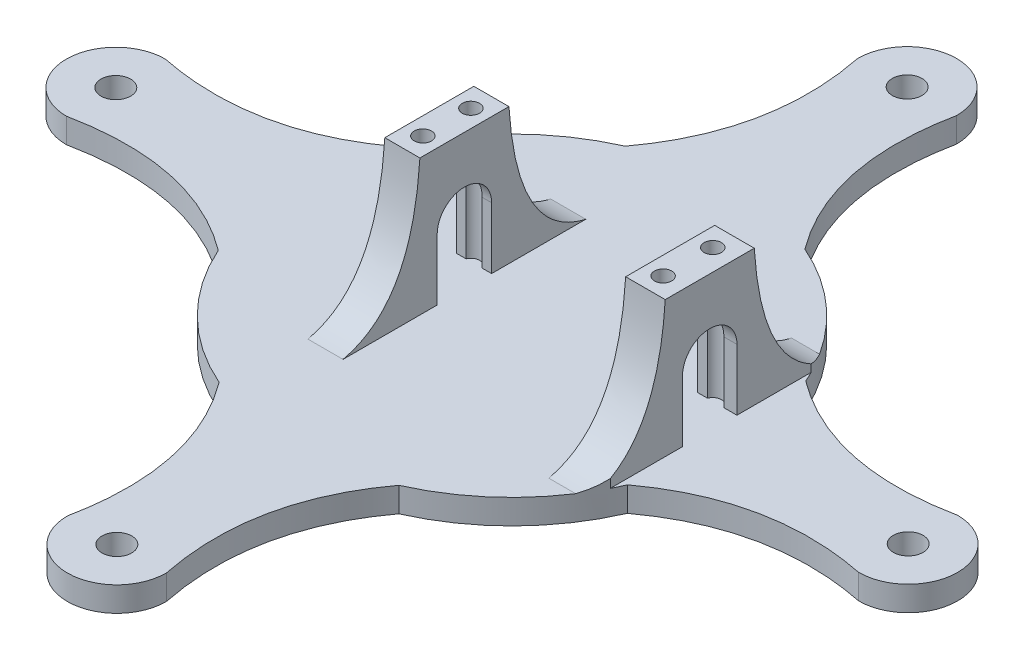
SolidWorks part; units mm, degrees
ref_plane "Vorne" through (0, 0, 0) normal (0, 0, 1) x (1, 0, 0)
ref_plane "Oben" through (0, 0, 0) normal (0, 1, 0) x (1, 0, 0)
ref_plane "Rechts" through (0, 0, 0) normal (1, 0, 0) x (0, 0, -1)
sketch "Skizze1" plane through (0, 0, 0) normal (0, 1, 0) x (1, 0, 0)
  circle A0 centre (0, 0) radius 45
  dimension "D1" = 90
extrude "Aufsatz-Linear austragen1" add sketch "Skizze1" along normal blind 5
sketch "Skizze3" plane through (0, 5, 0) normal (0, 1, 0) x (1, 0, 0)
  line L1 (-16.5343, 8.8163) -> (-8.5343, 8.8163)
  line L2 (-16.5343, 8.8163) -> (-16.5343, -9.1837)
  line L3 (-16.5343, -9.1837) -> (-8.5343, -9.1837)
  line L4 (-8.5343, 8.8163) -> (-8.5343, -9.1837)
  line L7 (32.1657, 8.8163) -> (40.1657, 8.8163)
  line L8 (32.1657, 8.8163) -> (32.1657, -9.1837)
  line L9 (32.1657, -9.1837) -> (40.1657, -9.1837)
  line L10 (40.1657, 8.8163) -> (40.1657, -9.1837)
extrude "Aufsatz-Linear austragen2" add sketch "Skizze3" along normal blind 27.5
sketch "Skizze4" plane through (-16.5343, 0, 0) normal (-1, 0, 0) x (0, 0, 1)
  line L0 (-8.8163, 5) -> (9.1837, 5) construction
  line L1 (-5.3163, 5) -> (5.6868, 5)
  line L2 (-5.3163, 5) -> (-5.3163, 17.4099)
  line L4 (5.6868, 5) -> (5.6868, 17.4099)
  line L5 (-8.8163, 32.5) -> (-8.8163, 5) construction
  line L6 (9.1837, 32.5) -> (9.1837, 5) construction
  arc A0 (5.6868, 17.4099) -> (-5.3163, 17.4099) centre (0.1853, 17.4099) ccw
  dimension "D1" = 3.5
  dimension "D2" = 3.4969
extrude "Schnitt-Linear austragen1" cut sketch "Skizze4" against normal blind 70.55
sketch "Skizze5" plane through (-16.5343, 0, 0) normal (-1, 0, 0) x (0, 0, 1)
  line L0 (45, 5) -> (-45, 5) construction
  line L2 (0.1837, 32.5) -> (0.1837, 5.7585) construction
  line L3 (-8.8163, 32.5) -> (-8.8163, 5)
  line L4 (-8.8163, 5) -> (-24.3573, 5)
  line L7 (-8.8163, 32.5) -> (9.1837, 32.5) construction
  line L8 (9.1837, 32.5) -> (9.1837, 5)
  line L9 (9.1837, 5) -> (24.7247, 5)
  spline S0 degree 2 poles (-8.8163, 32.5) (-10.3725, 8.1673) (-24.3573, 5) knots 0 0 0 1 1 1
  spline S1 degree 2 poles (9.1837, 32.5) (10.7399, 8.1673) (24.7247, 5) knots 0 0 0 1 1 1
extrude "Aufsatz-Linear austragen3" add sketch "Skizze5" against normal blind 56.7
sketch "Skizze6" plane through (0, 0, 0) normal (0, -1, 0) x (1, 0, 0)
  line L0 (36.0377, 26.9496) -> (42.7782, 28.6307)
  line L1 (42.7782, 28.6307) -> (51.7768, -24.2777)
  line L2 (51.7768, -24.2777) -> (37.779, -29.7768)
  line L3 (37.779, -29.7768) -> (35.3419, -27.8559)
  arc A0 (35.3419, -27.8559) -> (36.0377, 26.9496) centre (0, 0) ccw
extrude "Schnitt-Linear austragen2" cut sketch "Skizze6" against normal blind 10
sketch "Skizze7" plane through (0, 0, -8.8163) normal (0, 0, 1) x (1, 0, 0)
  line L0 (37.5991, 5) -> (-16.5343, 5) construction
  line L1 (-8.5343, 32.5) -> (32.1657, 32.5)
  line L2 (-8.5343, 32.5) -> (-8.5343, 5)
  line L3 (-8.5343, 5) -> (32.1657, 5)
  line L4 (32.1657, 32.5) -> (32.1657, 5)
extrude "Schnitt-Linear austragen3" cut sketch "Skizze7" along normal through all both and the other way through all
sketch "Skizze8" plane through (0, 32.5, 0) normal (0, 1, 0) x (1, 0, 0)
  line L0 (-16.5343, 8.8163) -> (-16.5343, -9.1837) construction
  line L1 (-16.5343, -9.1837) -> (-8.5343, -9.1837) construction
  line L2 (-8.5343, 8.8163) -> (-16.5343, 8.8163) construction
  circle A0 centre (-12.9843, 4.6663) radius 1.75
  circle A1 centre (-12.9843, -5.0337) radius 1.75
  circle A2 centre (35.8152, -5.2654) radius 1.75
  circle A3 centre (35.8627, 4.7345) radius 1.75
  arc A5 (37.5674, -4.0195) -> (37.5555, -6.5278) centre (35.8152, -5.2654) ccw construction
  arc A6 (37.6149, 5.9804) -> (37.603, 3.4721) centre (35.8627, 4.7345) ccw construction
  dimension "D1" = 3.55
  dimension "D2" = 3.55
  dimension "D3" = 4.15
  dimension "D4" = 4.15
  dimension "D5" = 0
  dimension "D6" = 0
  dimension "D7" = 0
  dimension "D9" = 3.5
  dimension "D10" = 3.5
  dimension "D11" = 3.5
  dimension "D12" = 3.5
extrude "Schnitt-Linear austragen4" cut sketch "Skizze8" against normal up to surface (27.5 mm away)
sketch "Skizze9" plane through (0, 5, 0) normal (0, 1, 0) x (1, 0, 0)
  line L0 (-0.1048, 89.9999) -> (-0.1048, 39.5894) construction
  line L1 (-18.2549, 41.131) -> (18.0453, 41.131)
  line L2 (41.131, 18.2549) -> (41.131, -18.0453)
  line L3 (-18.0453, -41.131) -> (18.2549, -41.131)
  line L4 (-41.131, 18.0453) -> (-41.131, -18.2549)
  arc A0 (9.8952, 79.9999) -> (-10.1048, 79.9999) centre (-0.1048, 79.9999) ccw
  arc A1 (37.8381, 24.3573) -> (37.5991, -24.7247) centre (0, 0) ccw construction
  arc A2 (79.9999, -9.8952) -> (79.9999, 10.1048) centre (79.9999, 0.1048) ccw
  arc A3 (-9.8952, -79.9999) -> (10.1048, -79.9999) centre (0.1048, -79.9999) ccw
  arc A4 (-79.9999, 9.8952) -> (-79.9999, -10.1048) centre (-79.9999, -0.1048) ccw
  spline S0 degree 2 poles (-10.1048, 79.9999) (-5.6591, 58.023) (-18.2549, 41.131) knots 0 0 0 1 1 1
  spline S1 degree 2 poles (9.8952, 79.9999) (5.4495, 58.023) (18.0453, 41.131) knots 0 0 0 1 1 1
  spline S2 degree 2 poles (79.9999, 10.1048) (58.023, 5.6591) (41.131, 18.2549) knots 0 0 0 1 1 1
  spline S3 degree 2 poles (79.9999, -9.8952) (58.023, -5.4495) (41.131, -18.0453) knots 0 0 0 1 1 1
  spline S4 degree 2 poles (10.1048, -79.9999) (5.6591, -58.023) (18.2549, -41.131) knots 0 0 0 1 1 1
  spline S5 degree 2 poles (-9.8952, -79.9999) (-5.4495, -58.023) (-18.0453, -41.131) knots 0 0 0 1 1 1
  spline S6 degree 2 poles (-79.9999, -10.1048) (-58.023, -5.6591) (-41.131, -18.2549) knots 0 0 0 1 1 1
  spline S7 degree 2 poles (-79.9999, 9.8952) (-58.023, 5.4495) (-41.131, 18.0453) knots 0 0 0 1 1 1
  point P28 (0, 0)
  dimension "D1" = 20
  dimension "D2" = 80
  dimension "D3" = 4
extrude "Aufsatz-Linear austragen4" add sketch "Skizze9" against normal through all
sketch "Skizze10" plane through (0, 32.5, 0) normal (0, 1, 0) x (1, 0, 0)
  line L0 (-8.5343, 24.3573) -> (-16.5343, 24.3573) construction
  line L1 (-8.5343, -24.7247) -> (-9.4367, -24.7247)
  line L2 (-8.5343, -24.7247) -> (-8.5343, 24.3573)
  line L3 (-8.5343, 24.3573) -> (-9.4367, 24.3573)
  line L4 (-9.4367, -24.7247) -> (-9.4367, 24.3573)
extrude "Schnitt-Linear austragen5" cut sketch "Skizze10" against normal up to surface (27.5 mm away) up to face at (16.8747, 5, 0.0771)
sketch "Skizze11" plane through (0, 5, 0) normal (0, 1, 0) x (1, 0, 0)
  circle A0 centre (-79.9999, -0.1048) radius 3
  circle A1 centre (-0.1048, 79.9999) radius 3
  circle A2 centre (79.9999, 0.1048) radius 3
  circle A3 centre (0.1048, -79.9999) radius 3
  dimension "D1" = 6
  dimension "D2" = 6
  dimension "D3" = 6
  dimension "D4" = 6
extrude "Schnitt-Linear austragen6" cut sketch "Skizze11" against normal blind 14.11
